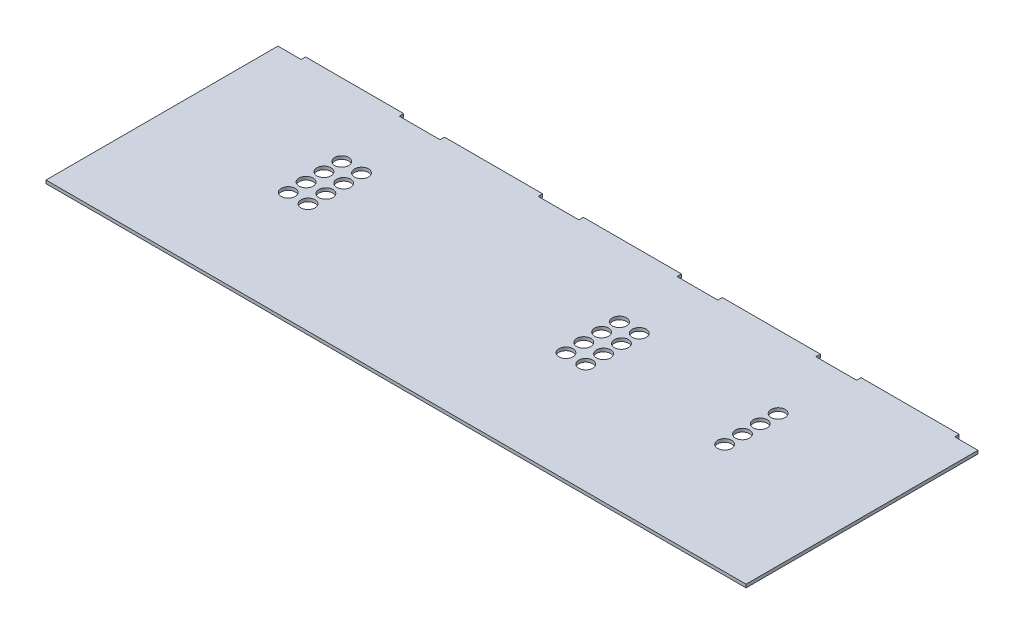
SolidWorks part; units mm, degrees
material "6061-T6 (SS)"
ref_plane "X-Y Datum" through (0, 0, 0) normal (0, 0, 1) x (1, 0, 0)
ref_plane "X-Z Datum" through (0, 0, 0) normal (0, 1, 0) x (1, 0, 0)
ref_plane "Y-Z Datum" through (0, 0, 0) normal (1, 0, 0) x (0, 0, -1)
sketch "Sketch1" plane through (0, 0, 0) normal (0, 1, 0) x (1, 0, 0)
  line L1 (-249.174, 82.55) -> (249.174, 82.55)
  line L2 (-249.174, 82.55) -> (-249.174, -82.55)
  line L3 (-249.174, -82.55) -> (249.174, -82.55)
  line L4 (249.174, 82.55) -> (249.174, -82.55)
  line L5 (-249.174, 82.55) -> (249.174, -82.55) construction
  line L6 (-249.174, -82.55) -> (249.174, 82.55) construction
  point P0 (0, 0)
  dimension "D1" = 498.348
  dimension "D2" = 165.1
extrude "Boss-Extrude1" add sketch "Sketch1" along normal mid plane 2.286
sketch "Sketch2" plane through (0, 0, -82.55) normal (0, 0, -1) x (-1, 0, 0)
  line L24 (-232.6386, -1.143) -> (-232.6386, 1.143)
  line L25 (-232.6386, 1.143) -> (-162.7886, 1.143)
  line L26 (-162.7886, -1.143) -> (-232.6386, -1.143)
  line L27 (-162.7886, 1.143) -> (-162.7886, -1.143)
extrude "Boss-Extrude2" add sketch "Sketch2" along normal blind 3.175
pattern_linear "LPattern1" count 5 spacing 98.8568 along (-1, 0, 0) of "Boss-Extrude2"
sketch "Sketch3" plane through (0, -1.143, 0) normal (0, -1, 0) x (1, 0, 0)
  circle A10 centre (-141.2367, 3.9751) radius 5
  circle A11 centre (-141.2367, -8.7249) radius 5
  circle A12 centre (-141.2367, -21.4249) radius 5
  circle A13 centre (-141.2367, -34.1249) radius 5
  circle A14 centre (-141.2367, -46.8249) radius 5
  circle A15 centre (-155.3337, -46.8249) radius 5
  circle A16 centre (-155.3337, -34.1249) radius 5
  circle A17 centre (-155.3337, -21.4249) radius 5
  circle A18 centre (-155.3337, -8.7249) radius 5
  circle A19 centre (-155.3337, 3.9751) radius 5
  circle A35 centre (155.3337, -46.8249) radius 5
  circle A36 centre (155.3337, -34.1249) radius 5
  circle A37 centre (155.3337, -21.4249) radius 5
  circle A38 centre (155.3337, -8.7249) radius 5
  circle A39 centre (155.3337, 3.9751) radius 5
  circle A40 centre (56.4769, 3.9751) radius 5
  circle A41 centre (56.4769, -8.7249) radius 5
  circle A42 centre (56.4769, -21.4249) radius 5
  circle A43 centre (56.4769, -34.1249) radius 5
  circle A44 centre (56.4769, -46.8249) radius 5
  circle A45 centre (42.3799, -46.8249) radius 5
  circle A46 centre (42.3799, -34.1249) radius 5
  circle A47 centre (42.3799, -21.4249) radius 5
  circle A48 centre (42.3799, -8.7249) radius 5
  circle A49 centre (42.3799, 3.9751) radius 5
  point P3 (0, 0)
extrude "Cut-Extrude1" cut sketch "Sketch3" against normal through all contours A19 | A10 | A11 | A18 | A12 | A17 | A13 | A16 | A40 | A41 | A49 | A48 | A42 | A47 | A43 | A46 | A39 | A38 | A37 | A36
